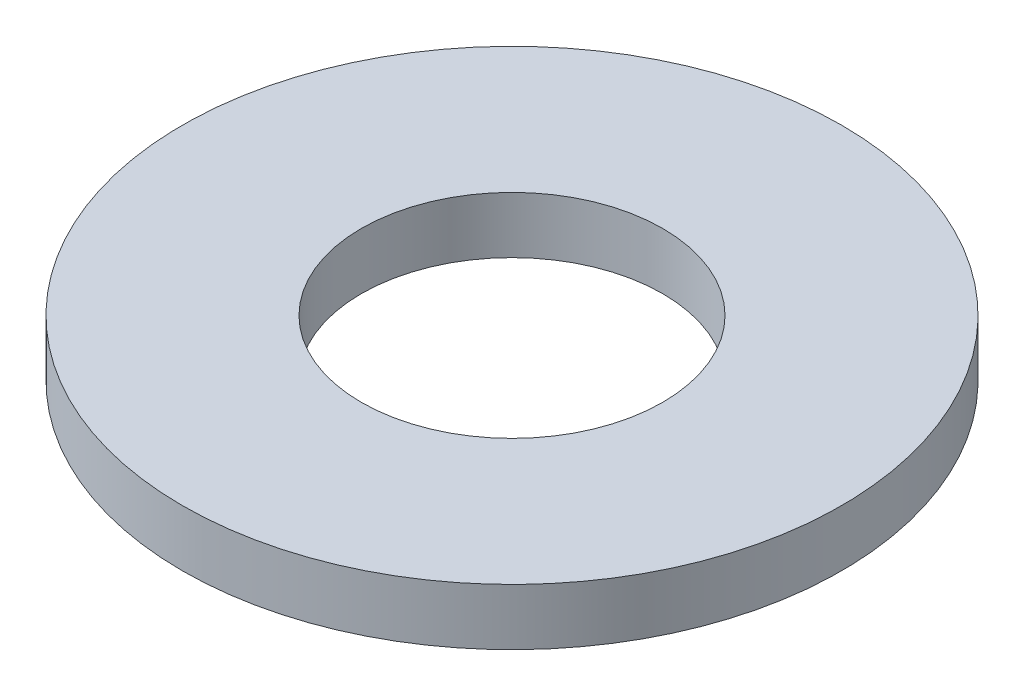
SolidWorks part; units mm, degrees
ref_plane "Front Plane" through (0, 0, 0) normal (0, 0, 1) x (1, 0, 0)
ref_plane "Top Plane" through (0, 0, 0) normal (0, 1, 0) x (1, 0, 0)
ref_plane "Right Plane" through (0, 0, 0) normal (1, 0, 0) x (0, 0, -1)
sketch "Sketch1" plane through (0, 0, 0) normal (0, 1, 0) x (1, 0, 0)
  circle A0 centre (0, 0) radius 8
  circle A1 centre (0, 0) radius 17.5
  dimension "D1" = 16
  dimension "D2" = 35
extrude "Boss-Extrude1" add sketch "Sketch1" along normal blind 3
